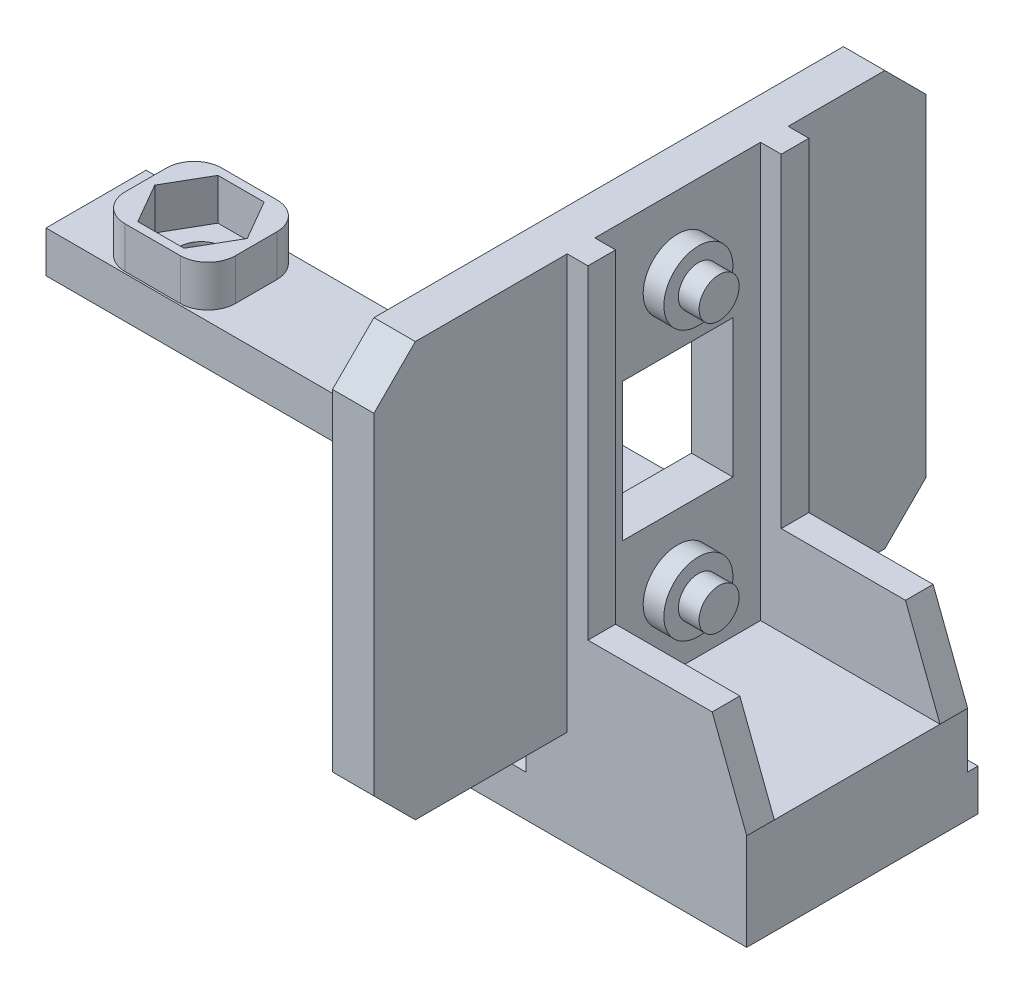
SolidWorks part; units mm, degrees
ref_plane "Front Plane" through (0, 0, 0) normal (0, 0, 1) x (1, 0, 0)
ref_plane "Top Plane" through (0, 0, 0) normal (0, 1, 0) x (1, 0, 0)
ref_plane "Right Plane" through (0, 0, 0) normal (1, 0, 0) x (0, 0, -1)
sketch "Sketch1" plane through (0, 0, 0) normal (0, 1, 0) x (1, 0, 0)
  line L0 (0, 0) -> (0, -16.75)
  line L1 (0, 0) -> (-56, 0)
  line L2 (0, 0) -> (0, 7.25)
  line L3 (0, 7.25) -> (-56, 7.25)
  line L4 (-56, 0) -> (-56, 7.25)
  line L5 (0, -16.75) -> (-16.5, -16.75)
  line L6 (-16.5, -16.75) -> (-16.5, 0)
  line L7 (0, 0) -> (11.5, 0)
  line L8 (11.5, 0) -> (11.5, -16.75)
  line L9 (11.5, -16.75) -> (0, -16.75)
  line L10 (-5, 0) -> (-5, -16.75)
  circle A0 centre (-48.4, 3.625) radius 1.6
  circle A1 centre (-7.6, 3.625) radius 1.6
  point P13 (-56, 3.625)
  dimension "D4" = 3.2
  dimension "D5" = 3.2
  dimension "D1" = 7.25
  dimension "D2" = 56
  dimension "D3" = 16.75
  dimension "D6" = 7.6
  dimension "D7" = 7.6
  dimension "D8" = 16.5
  dimension "D9" = 16.5
  dimension "D10" = 11.5
extrude "Boss-Extrude1" add sketch "Sketch1" along normal blind 3 contours L4 L1 L2 L3 A1 A0 | L1 L10 L5 L0 | L9 L8 L7 L0 | L10 L1 L6 L5
sketch "Sketch2" plane through (0, 3, 0) normal (0, 1, 0) x (1, 0, 0)
  line L1 (-52.4, 7.125) -> (-44.4, 7.125)
  line L2 (-52.4, 7.125) -> (-52.4, 0.125)
  line L3 (-52.4, 0.125) -> (-44.4, 0.125)
  line L4 (-44.4, 7.125) -> (-44.4, 0.125)
  line L5 (-52.4, 7.125) -> (-44.4, 0.125) construction
  line L6 (-52.4, 0.125) -> (-44.4, 7.125) construction
  line L7 (-46.7257, 0.725) -> (-45.0514, 3.625)
  line L8 (-45.0514, 3.625) -> (-46.7257, 6.525)
  line L9 (-46.7257, 6.525) -> (-50.0743, 6.525)
  line L10 (-50.0743, 6.525) -> (-51.7486, 3.625)
  line L11 (-51.7486, 3.625) -> (-50.0743, 0.725)
  line L12 (-50.0743, 0.725) -> (-46.7257, 0.725)
  line L13 (-11.6, 7.125) -> (-3.6, 7.125)
  line L14 (-11.6, 7.125) -> (-11.6, 0.125)
  line L15 (-11.6, 0.125) -> (-3.6, 0.125)
  line L16 (-3.6, 7.125) -> (-3.6, 0.125)
  line L17 (-11.6, 7.125) -> (-3.6, 0.125) construction
  line L18 (-11.6, 0.125) -> (-3.6, 7.125) construction
  line L19 (-5.9257, 0.725) -> (-4.2514, 3.625)
  line L20 (-4.2514, 3.625) -> (-5.9257, 6.525)
  line L21 (-5.9257, 6.525) -> (-9.2743, 6.525)
  line L22 (-9.2743, 6.525) -> (-10.9486, 3.625)
  line L23 (-10.9486, 3.625) -> (-9.2743, 0.725)
  line L24 (-9.2743, 0.725) -> (-5.9257, 0.725)
  circle A0 centre (-48.4, 3.625) radius 2.9 construction
  circle A1 centre (-7.6, 3.625) radius 2.9 construction
  point P0 (-48.4, 3.625)
  point P7 (-7.6, 3.625)
  dimension "D1" = 8
  dimension "D2" = 7
  dimension "D3" = 5.8
  dimension "D4" = 7
  dimension "D5" = 8
  dimension "D6" = 5.8
extrude "Boss-Extrude2" add sketch "Sketch2" along normal blind 3
fillet "Fillet1" radius 2 8 edges at (-11.6, 4.5, -7.125) (-11.6, 4.5, -0.125) (-3.6, 4.5, -0.125) (-3.6, 4.5, -7.125) (-44.4, 4.5, -0.125) (-44.4, 4.5, -7.125) (-52.4, 4.5, -7.125) (-52.4, 4.5, -0.125)
sketch "Sketch3" plane through (0, 3, 0) normal (0, 1, 0) x (1, 0, 0)
  line L0 (11.5, -0.75) -> (-4.5, -0.75)
  line L1 (11.5, 0) -> (11.5, -16.75) construction
  line L2 (-4.5, -0.75) -> (-4.5, -16.75)
  line L3 (11.5, -16.75) -> (-16.5, -16.75) construction
  line L4 (-4.5, -16.75) -> (11.5, -16.75)
  line L5 (11.5, -16.75) -> (11.5, -0.75)
  dimension "D1" = 16
  dimension "D2" = 16
extrude "Boss-Extrude3" add sketch "Sketch3" along normal blind 4
sketch "Sketch5" plane through (-4.5, 0, 0) normal (-1, 0, 0) x (0, 0, 1)
  line L0 (0.75, 7) -> (16.75, 7) construction
  line L1 (0.75, 7) -> (16.75, 7)
  line L2 (16.75, 7) -> (30.75, 7)
  line L3 (30.75, 7) -> (30.75, 37)
  line L4 (30.75, 37) -> (-9.25, 37)
  line L5 (-9.25, 37) -> (-9.25, 7)
  line L6 (-9.25, 7) -> (0.75, 7)
  line L7 (0.75, 7) -> (0.75, 3) construction
  line L8 (16.75, 7) -> (16.75, 3) construction
  dimension "D1" = 10
  dimension "D2" = 30
  dimension "D3" = 14
extrude "Boss-Extrude4" add sketch "Sketch5" against normal blind 3
sketch "Sketch6" plane through (0, 0, 16.75) normal (0, 0, 1) x (1, 0, 0)
  line L0 (-1.5, 37) -> (0, 37)
  line L1 (0, 37) -> (11.5, 7)
  line L2 (11.5, 7) -> (-1.5, 7)
  line L3 (-1.5, 7) -> (-1.5, 37)
extrude "Boss-Extrude5" add sketch "Sketch6" against normal blind 2
sketch "Sketch7" plane through (0, 0, 0.75) normal (0, 0, -1) x (-1, 0, 0)
  line L4 (1.5, 37) -> (0, 37)
  line L5 (0, 37) -> (-11.5, 7)
  line L6 (-11.5, 7) -> (1.5, 7)
  line L7 (1.5, 7) -> (1.5, 37)
  line L8 (1.5, 37) -> (0, 37)
  line L9 (0, 37) -> (-11.5, 7)
  line L10 (-11.5, 7) -> (1.5, 7)
  line L11 (1.5, 7) -> (1.5, 37)
  point P2 (0, 0)
  dimension "D1" = 0
extrude "Boss-Extrude6" add sketch "Sketch7" against normal blind 2
chamfer "Chamfer1" distance 3 angle 45 4 edges at (-3, 7, -9.25) (-3, 7, 30.75) (-3, 37, 30.75) (-3, 37, -9.25)
sketch "Sketch8" plane through (-1.5, 0, 0) normal (1, 0, 0) x (0, 0, -1)
  line L0 (-14.75, 7) -> (-14.75, 37) construction
  line L1 (-12.75, 27) -> (-4.75, 27)
  line L2 (-12.75, 27) -> (-12.75, 17)
  line L3 (-12.75, 17) -> (-4.75, 17)
  line L4 (-4.75, 27) -> (-4.75, 17)
  line L5 (-14.75, 37) -> (-2.75, 37) construction
  dimension "D1" = 10
  dimension "D2" = 8
  dimension "D3" = 2
  dimension "D4" = 10
extrude "Cut-Extrude1" cut sketch "Sketch8" against normal blind 10
sketch "Sketch9" plane through (-1.5, 0, 0) normal (1, 0, 0) x (0, 0, -1)
  line L0 (-12.75, 22) -> (-4.75, 22) construction
  line L1 (-12.75, 27) -> (-12.75, 17) construction
  line L2 (-4.75, 17) -> (-4.75, 27) construction
  line L3 (-8.75, 37) -> (-8.75, 7) construction
  line L4 (-14.75, 37) -> (-2.75, 37) construction
  line L5 (-14.75, 7) -> (-2.75, 7) construction
  circle A1 centre (-8.75, 31.75) radius 1.45
  circle A3 centre (-8.75, 12.25) radius 1.45
  dimension "D1" = 9.75
extrude "Boss-Extrude7" add sketch "Sketch9" along normal blind 3
sketch "Sketch11" plane through (-1.5, 0, 0) normal (1, 0, 0) x (0, 0, -1)
  circle A0 centre (-8.75, 31.75) radius 2.5
  circle A1 centre (-8.75, 12.25) radius 2.5
extrude "Boss-Extrude8" add sketch "Sketch11" along normal blind 1.5
sketch "Sketch13" plane through (0, 0, 0.75) normal (0, 0, -1) x (-1, 0, 0)
  line L0 (0, 37) -> (0, 13.5217)
  line L1 (0, 13.5217) -> (-9, 13.5217)
  line L2 (0, 37) -> (-11.5, 7) construction
  dimension "D1" = 9
extrude "Cut-Extrude3" cut sketch "Sketch13" against normal blind 2 and the other way through all flip side to cut
sketch "Sketch14" plane through (0, 0, 16.75) normal (0, 0, 1) x (1, 0, 0)
  line L0 (0, 37) -> (0, 13.5217)
  line L1 (0, 13.5217) -> (9, 13.5217)
  line L2 (11.5, 7) -> (0, 37) construction
  dimension "D1" = 9
extrude "Cut-Extrude4" cut sketch "Sketch14" against normal blind 2 and the other way through all
